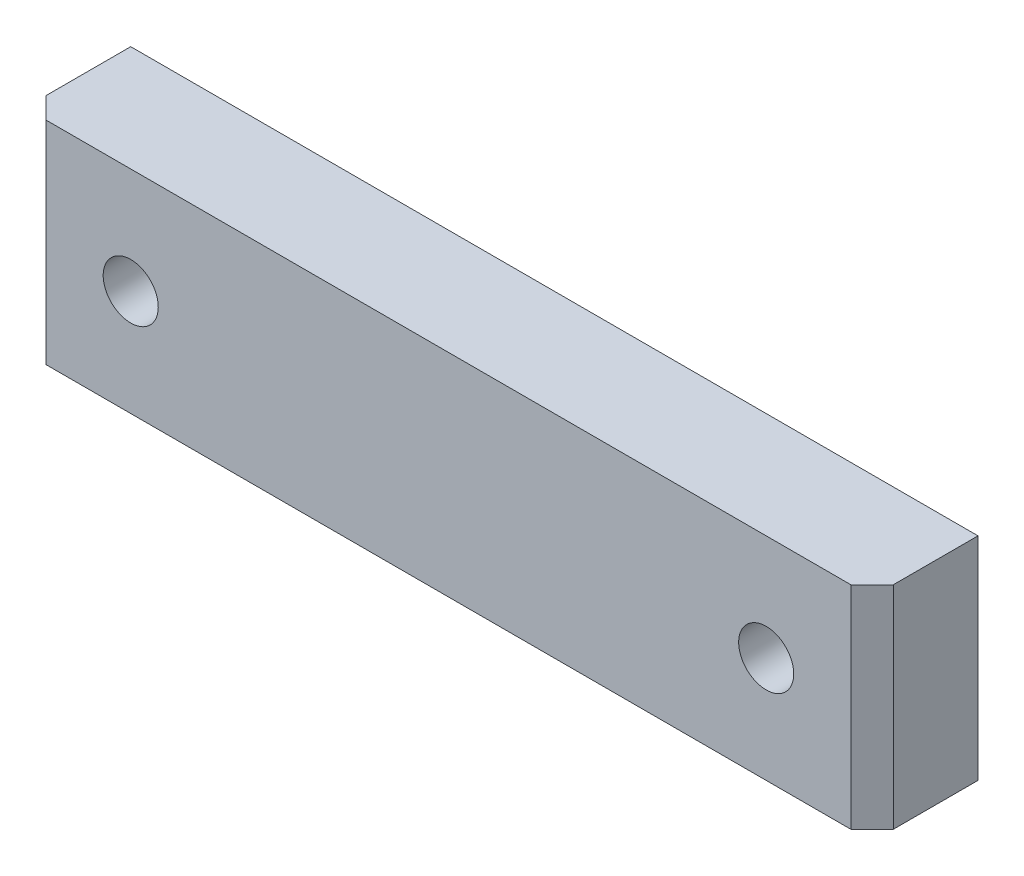
SolidWorks part; units mm, degrees
ref_plane "Спереди" through (0, 0, 0) normal (0, 0, 1) x (1, 0, 0)
ref_plane "Сверху" through (0, 0, 0) normal (0, 1, 0) x (1, 0, 0)
ref_plane "Справа" through (0, 0, 0) normal (1, 0, 0) x (0, 0, -1)
other "Configuration Table"
sketch "Эскиз2" plane through (0, 0, 0) normal (0, 0, 1) x (1, 0, 0)
  line L0 (-30, 0) -> (0, 0) construction
  line L1 (-40, -10) -> (40, -10)
  line L2 (-40, -10) -> (-40, 10)
  line L3 (-40, 10) -> (40, 10)
  line L4 (40, -10) -> (40, 10)
  line L5 (-40, -10) -> (40, 10) construction
  line L6 (-40, 10) -> (40, -10) construction
  line L7 (0, 0) -> (30, 0) construction
  circle A0 centre (-30, 0) radius 2.6
  circle A1 centre (30, 0) radius 2.6
  point P0 (0, 0)
  dimension "D4" = 5.2
  dimension "D1" = 20
  dimension "D2" = 80
  dimension "D3" = 60
extrude "Бобышка-Вытянуть1" add sketch "Эскиз2" along normal blind 10
sketch "Эскиз3" plane through (0, 0, 0) normal (0, 0, -1) x (-1, 0, 0)
  line L0 (40, -10) -> (-40, -10) construction
  line L1 (-15, 0) -> (15, 0)
  line L2 (-15, 0) -> (-15, -10)
  line L3 (-15, -10) -> (15, -10)
  line L4 (15, 0) -> (15, -10)
  point P6 (0, 0)
  dimension "D1" = 30
extrude "Вырез-Вытянуть1" cut sketch "Эскиз3" against normal blind 5
chamfer "Фаска1" distance 2 angle 45 2 edges at (40, 0, 10) (-40, 0, 10)
